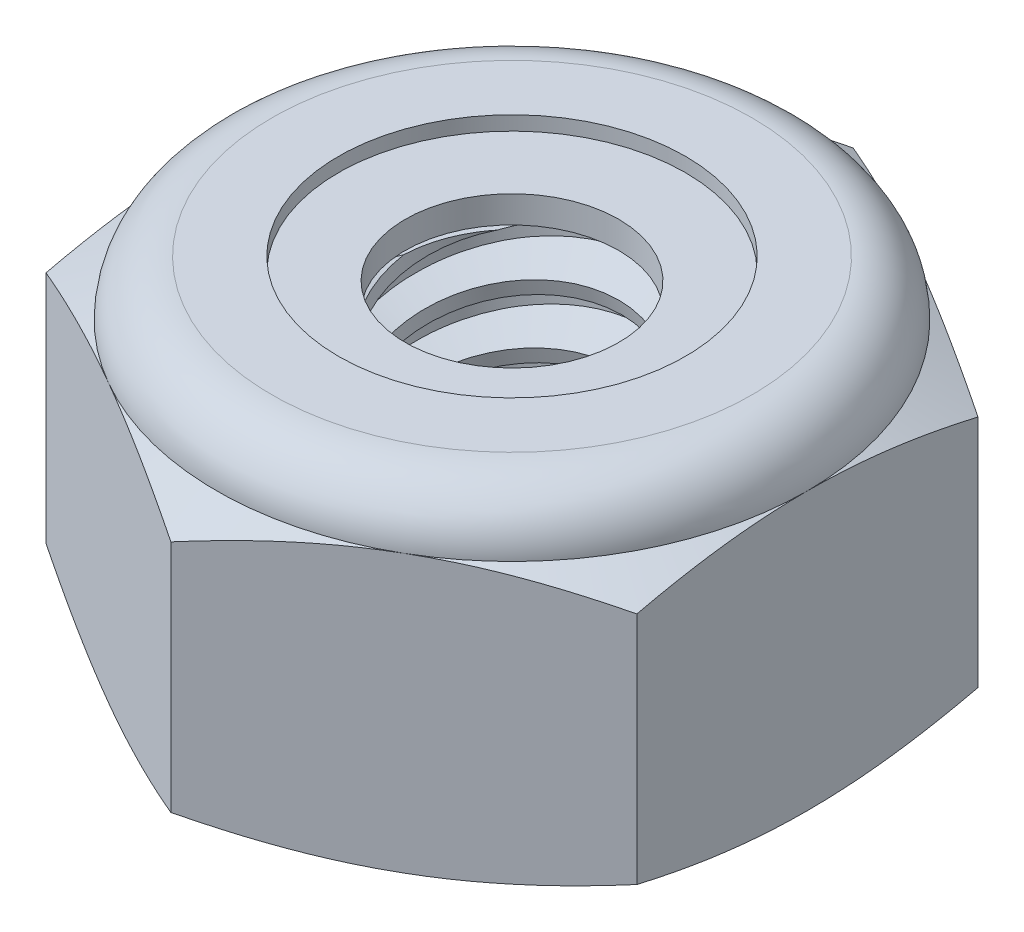
SolidWorks part; units mm, degrees
material "Alloy Steel"
ref_plane "Front" through (0, 0, 0) normal (0, 0, 1) x (1, 0, 0)
ref_plane "Top" through (0, 0, 0) normal (0, 1, 0) x (1, 0, 0)
ref_plane "Right" through (0, 0, 0) normal (1, 0, 0) x (0, 0, -1)
sketch "Sketch1" plane through (0, 0, 0) normal (0, 1, 0) x (1, 0, 0)
  line L1 (0, 3.6662) -> (-3.175, 1.8331)
  line L2 (-3.175, 1.8331) -> (-3.175, -1.8331)
  line L3 (-3.175, -1.8331) -> (0, -3.6662)
  line L4 (0, -3.6662) -> (3.175, -1.8331)
  line L5 (3.175, -1.8331) -> (3.175, 1.8331)
  line L6 (3.175, 1.8331) -> (0, 3.6662)
  circle A0 centre (0, 0) radius 3.175 construction
  dimension "Hex Flats" = 6.35
extrude "Extrude1" add sketch "Sketch1" along normal blind 3.5719
sketch "Sketch2" plane through (0, 0, 0) normal (1, 0, 0) x (0, 0, -1)
  line L0 (-1.4224, 0) -> (-1.4224, 3.5719) construction
  line L1 (0, 0) -> (1.4224, 0)
  line L2 (0, 0) -> (0, 3.5719)
  line L3 (0, 3.5719) -> (1.4224, 3.5719)
  line L4 (1.4224, 0) -> (1.4224, 3.5719)
  line L5 (-1.8331, 3.5719) -> (1.8331, 3.5719) construction
  line L7 (0, -1.4224) -> (0, 0) construction
  dimension "Thread Dia" = 2.8448
revolve "Revolve1" add sketch "Sketch2" angle 360 about L7
sketch "Sketch3" plane through (0, 0, 0) normal (1, 0, 0) x (0, 0, -1)
  line L0 (1.4224, 3.5719) -> (-1.4224, 3.5719) construction
  line L1 (-1.4224, 3.5719) -> (-1.4224, 2.9369) construction
  line L2 (-1.4224, 2.9369) -> (1.4224, 3.5719) construction
  line L3 (1.4224, 3.5719) -> (1.4397, 3.4944) construction
  line L4 (1.4397, 3.4944) -> (1.5607, 2.9521)
  line L5 (1.5607, 2.9521) -> (1.1821, 3.0709)
  line L6 (1.1821, 3.0709) -> (1.1475, 3.2259)
  line L7 (1.1475, 3.2259) -> (1.4397, 3.4944)
  line L8 (1.1648, 3.1484) -> (1.5002, 3.2233) construction
  line L9 (1.4224, 3.5719) -> (1.4224, 3.2059) construction
  line L10 (1.4224, 3.2059) -> (-1.4224, 2.5709) construction
  line L11 (-1.4224, 2.5709) -> (-1.4224, 2.9369) construction
  line L12 (-0.1526, 3.5719) -> (0.1526, 2.2049) construction
  line L13 (-1.4224, 0) -> (-1.4224, 3.5719) construction
  line L14 (0, 3.5719) -> (1.4224, 3.5719) construction
  line L15 (1.4224, 0) -> (1.4224, 3.5719) construction
  point P13 (0, 2.8884)
  dimension "D1" = 0.0794
  dimension "D2" = 0.1588
  dimension "Thread Pitch" = 0.635
  dimension "D4" = 60
  dimension "D5" = 0.635
revolve "Cut-Revolve1" cut sketch "Sketch3" angle 360 about L12
pattern_linear "LPattern1" count 6 spacing 0.635 along (0, -1, 0) count 2 spacing 0.635 along (0, 1, 0) of "Cut-Revolve1"
sketch "Sketch4" plane through (0, 0, 0) normal (1, 0, 0) x (0, 0, -1)
  line L0 (0, 3.5719) -> (1.4224, 3.5719)
  line L1 (1.4224, 3.5719) -> (1.1475, 3.4437)
  line L2 (1.1475, 3.4437) -> (1.1475, 0.1282)
  line L3 (1.1475, 0.1282) -> (1.4224, 0)
  line L4 (1.4224, 0) -> (0, 0)
  line L5 (0, 0) -> (0, 3.5719)
  line L6 (1.4224, 0) -> (1.4224, 3.5719) construction
  line L7 (0, 3.5719) -> (1.4224, 3.5719) construction
  line L8 (0, 0) -> (1.4224, 0) construction
  line L9 (0, 0) -> (0, 3.5719) construction
  line L10 (0, 3.5719) -> (0, 3.8752) construction
  dimension "D1" = 25
revolve "Cut-Revolve2" cut sketch "Sketch4" angle 360 about L10
combine bodies "Combine1" operation type subtract main body 112 bodies to subtract 111
sketch "Sketch5" plane through (0, 0, 0) normal (1, 0, 0) x (0, 0, -1)
  line L0 (0, 0) -> (3.175, 0)
  line L1 (3.175, 0) -> (3.6662, 0.229)
  line L2 (3.6662, 0.229) -> (3.6662, 2.7475)
  line L3 (3.6662, 2.7475) -> (3.175, 2.9766)
  line L4 (2.5797, 3.5719) -> (2.5797, 4.8419)
  line L5 (2.5797, 4.8419) -> (4.9362, 4.8419)
  line L6 (4.9362, 4.8419) -> (4.9362, -1.27)
  line L7 (4.9362, -1.27) -> (0, -1.27)
  line L8 (0, -1.27) -> (0, 0)
  line L9 (3.175, 2.9766) -> (3.175, 0) construction
  line L10 (0, 0) -> (1.4224, 0) construction
  line L13 (3.6662, 1.4883) -> (4.9362, 1.4883) construction
  line L14 (3.6662, 3.5719) -> (3.6662, 0) construction
  line L15 (0, 0) -> (0, 4.8419) construction
  line L20 (0, 4.8419) -> (2.5797, 4.8419) construction
  line L22 (0, 3.5719) -> (1.4224, 3.5719) construction
  arc A0 (3.175, 2.9766) -> (2.5797, 3.5719) centre (2.5797, 2.9766) ccw
  dimension "D1" = 25
  dimension "D2" = 1.27
  dimension "D3" = 3.5719
  dimension "D4" = 0.5953
revolve "Cut-Revolve3" cut sketch "Sketch5" angle 360 about L15
sketch "Sketch6" plane through (0, 0, 0) normal (1, 0, 0) x (0, 0, -1)
  line L0 (0, 2.9766) -> (3.0226, 2.9766)
  line L1 (2.5797, 3.4195) -> (1.8636, 3.4195)
  line L2 (0, 4.8419) -> (0, 2.9766)
  line L3 (1.8636, 4.8419) -> (0, 4.8419)
  line L4 (0, 4.8419) -> (2.5797, 4.8419) construction
  line L5 (0, 0) -> (0, 4.8419) construction
  line L6 (0, 4.8419) -> (0, 44.323) construction
  line L7 (1.8636, 3.4195) -> (1.8636, 4.8419)
  line L8 (2.5797, 3.5719) -> (2.5797, 3.4195) construction
  line L9 (1.8636, 3.4195) -> (1.1475, 3.4195) construction
  line L10 (1.1475, 3.4195) -> (1.1475, 3.4437) construction
  arc A0 (3.0226, 2.9766) -> (2.5797, 3.4195) centre (2.5797, 2.9766) ccw
  arc A1 (3.175, 2.9766) -> (2.5797, 3.5719) centre (2.5797, 2.9766) ccw construction
  dimension "D1" = 0.1524
revolve "Cut-Revolve4" cut sketch "Sketch6" angle 360 about L6
sketch "Sketch7" plane through (0, 0, 0) normal (1, 0, 0) x (0, 0, -1)
  line L0 (1.1475, 3.0528) -> (2.9384, 3.0528)
  line L1 (2.5797, 3.3433) -> (1.1475, 3.3433)
  line L2 (1.1475, 3.3433) -> (1.1475, 3.0528)
  line L3 (1.1475, 3.0528) -> (0, 3.0528) construction
  line L4 (0, 3.0528) -> (0, 3.3433) construction
  line L5 (0, 3.3433) -> (1.1475, 3.3433) construction
  line L6 (1.1475, 3.0528) -> (1.1475, 2.9766) construction
  line L7 (0, 2.9766) -> (3.0226, 2.9766) construction
  line L8 (2.5797, 3.3433) -> (2.5797, 3.4195) construction
  arc A0 (2.9384, 3.0528) -> (2.5797, 3.3433) centre (2.5797, 2.9766) ccw
  arc A2 (3.0226, 2.9766) -> (2.5797, 3.4195) centre (2.5797, 2.9766) ccw construction
  dimension "D1" = 0.0762
revolve "Revolve2" add sketch "Sketch7" angle 360 about L4
equation "\"D1@Sketch3\"=\"Thread Pitch@Sketch3\"/8"
equation "\"D2@Sketch3\"=\"Thread Pitch@Sketch3\"/4"
equation "\"D5@Sketch3\"=\"Thread Pitch@Sketch3\""
equation "\"D4@LPattern1\"=\"Thread Pitch@Sketch3\""
equation "\"D3@LPattern1\"=\"Thread Pitch@Sketch3\""
equation "\"D1@LPattern1\"=\"Height@Extrude1\"/\"Thread Pitch@Sketch3\""
equation "\"D4@Sketch5\"=\"Height@Extrude1\"/6"
